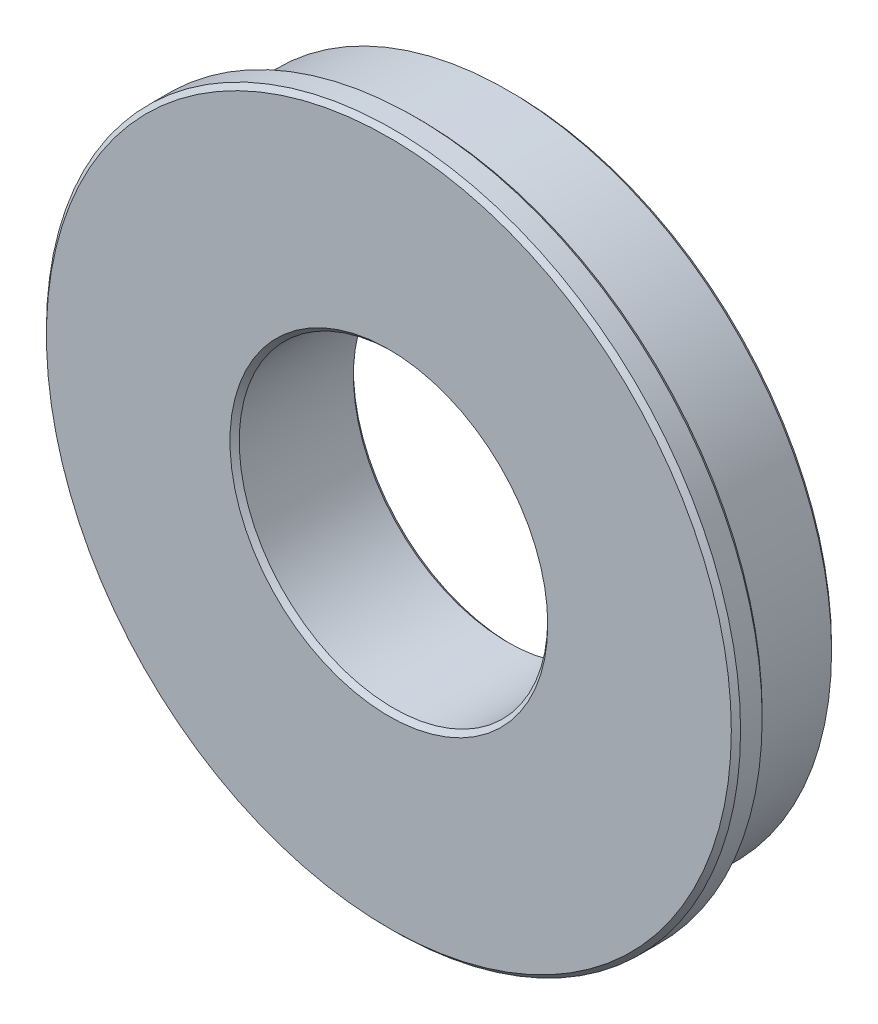
SolidWorks part; units mm, degrees
ref_plane "前视基准面" through (0, 0, 0) normal (0, 0, 1) x (1, 0, 0)
ref_plane "上视基准面" through (0, 0, 0) normal (0, 1, 0) x (1, 0, 0)
ref_plane "右视基准面" through (0, 0, 0) normal (1, 0, 0) x (0, 0, -1)
sketch "草图1" plane through (0, 0, 0) normal (0, 0, 1) x (1, 0, 0)
  circle A0 centre (0, 0) radius 21
  circle A1 centre (0, 0) radius 10
  dimension "D1" = 20
  dimension "D2" = 42
extrude "凸台-拉伸1" add sketch "草图1" along normal mid plane 8
sketch "草图2" plane through (0, 0, 4) normal (0, 0, 1) x (1, 0, 0)
  circle A0 centre (0, 0) radius 22.5
  circle A1 centre (0, 0) radius 10 construction
  circle A2 centre (0, 0) radius 10
  dimension "D1" = 45
extrude "凸台-拉伸2" add sketch "草图2" against normal blind 2
chamfer "倒角1" distance 0.3 angle 45 5 edges at (10, 0, 4) (22.5, 0, 2) (22.5, 0, 4) (10, 0, -4) (21, 0, -4)
